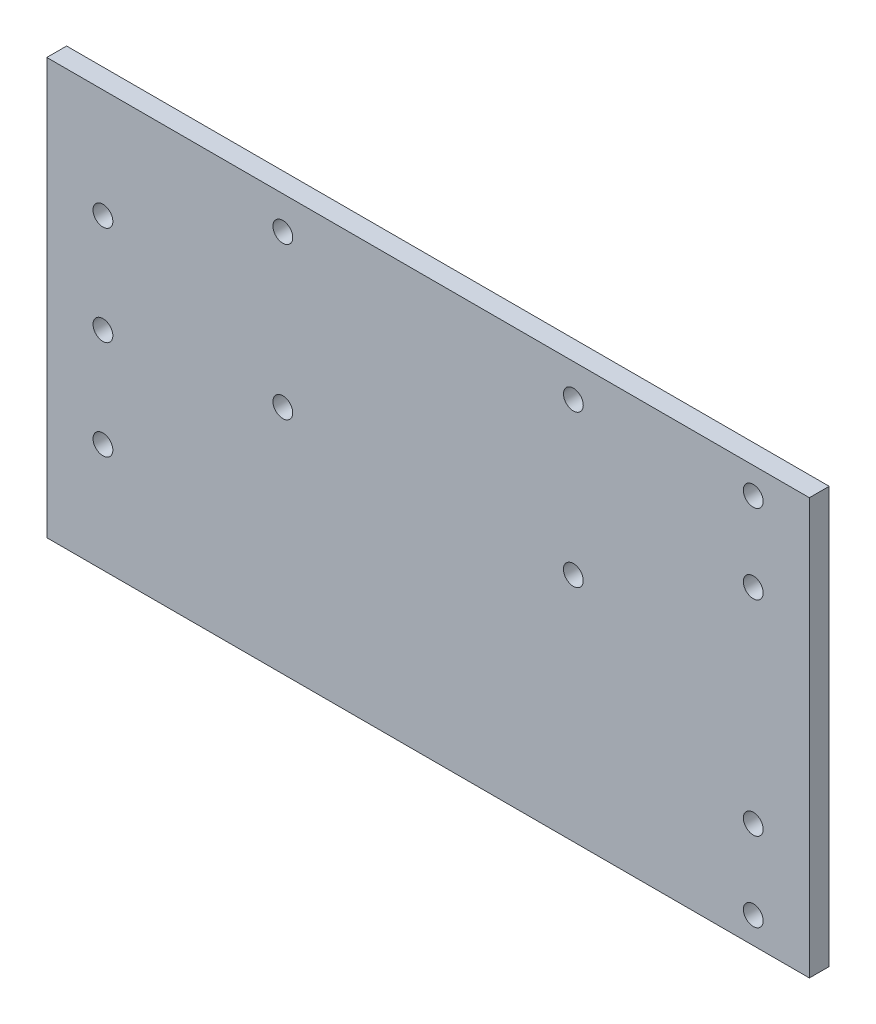
SolidWorks part; units mm, degrees
material "Thornel Mat VMA"
ref_plane "前视基准面" through (0, 0, 0) normal (0, 0, 1) x (1, 0, 0)
ref_plane "上视基准面" through (0, 0, 0) normal (0, 1, 0) x (1, 0, 0)
ref_plane "右视基准面" through (0, 0, 0) normal (1, 0, 0) x (0, 0, -1)
sketch "草图1" plane through (0, 0, 0) normal (0, 0, 1) x (1, 0, 0)
  line L1 (-57.75, 31.5) -> (57.75, 31.5)
  line L2 (-57.75, 31.5) -> (-57.75, -31.5)
  line L3 (-57.75, -31.5) -> (57.75, -31.5)
  line L4 (57.75, 31.5) -> (57.75, -31.5)
  line L5 (-57.75, 31.5) -> (57.75, -31.5) construction
  line L6 (-57.75, -31.5) -> (57.75, 31.5) construction
  point P0 (0, 0)
  dimension "D1" = 115.5
  dimension "D2" = 63
extrude "凸台-拉伸1" add sketch "草图1" along normal blind 3
sketch "草图2" plane through (0, 0, 3) normal (0, 0, 1) x (1, 0, 0)
  line L0 (0, 31.5) -> (0, -31.5) construction
  line L1 (57.75, 31.5) -> (-57.75, 31.5) construction
  line L2 (-57.75, -31.5) -> (57.75, -31.5) construction
  line L3 (0, -31.5) -> (0, 0) construction
  line L4 (-49.25, 27.5) -> (49.25, 27.5) construction
  line L5 (-49.25, 27.5) -> (-49.25, -27.5) construction
  line L6 (-49.25, -27.5) -> (49.25, -27.5) construction
  line L7 (49.25, 27.5) -> (49.25, -27.5) construction
  line L8 (-49.25, 27.5) -> (49.25, -27.5) construction
  line L9 (-49.25, -27.5) -> (49.25, 27.5) construction
  line L11 (49.25, 15.5) -> (-49.25, 15.5) construction
  line L12 (49.25, 15.5) -> (49.25, -15.5) construction
  line L13 (49.25, -15.5) -> (-49.25, -15.5) construction
  line L14 (-49.25, 15.5) -> (-49.25, -15.5) construction
  line L15 (49.25, 15.5) -> (-49.25, -15.5) construction
  line L16 (49.25, -15.5) -> (-49.25, 15.5) construction
  circle A3 centre (49.25, 27.5) radius 1.5
  circle A4 centre (49.25, -27.5) radius 1.5
  circle A9 centre (49.25, 15.5) radius 1.5
  circle A10 centre (49.25, -15.5) radius 1.5
  circle A13 centre (-49.25, 0) radius 1.5
  circle A14 centre (-49.25, 15) radius 1.5
  circle A15 centre (-49.25, -15) radius 1.5
  point P6 (0, 0)
  point P27 (0, 0)
  dimension "D1" = 98.5
  dimension "D3" = 3
  dimension "D4" = 31
  dimension "D5" = 15
  dimension "D2" = 55
  dimension "D6" = 15
  dimension "D7" = 12.5
extrude "切除-拉伸1" cut sketch "草图2" against normal through all
sketch "草图3" plane through (0, 0, 3) normal (0, 0, 1) x (1, 0, 0)
  line L0 (-57.75, -31.5) -> (57.75, -31.5) construction
  line L1 (-22, 26.5) -> (22, 26.5) construction
  line L2 (-22, 26.5) -> (-22, 3.5) construction
  line L3 (-22, 3.5) -> (22, 3.5) construction
  line L4 (22, 26.5) -> (22, 3.5) construction
  line L5 (-22, 26.5) -> (22, 3.5) construction
  line L6 (-22, 3.5) -> (22, 26.5) construction
  line L8 (0, 15) -> (0, -31.5) construction
  circle A0 centre (-22, 26.5) radius 1.5
  circle A1 centre (22, 26.5) radius 1.5
  circle A2 centre (22, 3.5) radius 1.5
  circle A3 centre (-22, 3.5) radius 1.5
  point P0 (0, 15)
  dimension "D3" = 3
  dimension "D4" = 46.5
  dimension "D1" = 44
  dimension "D2" = 23
extrude "切除-拉伸2" cut sketch "草图3" against normal through all
